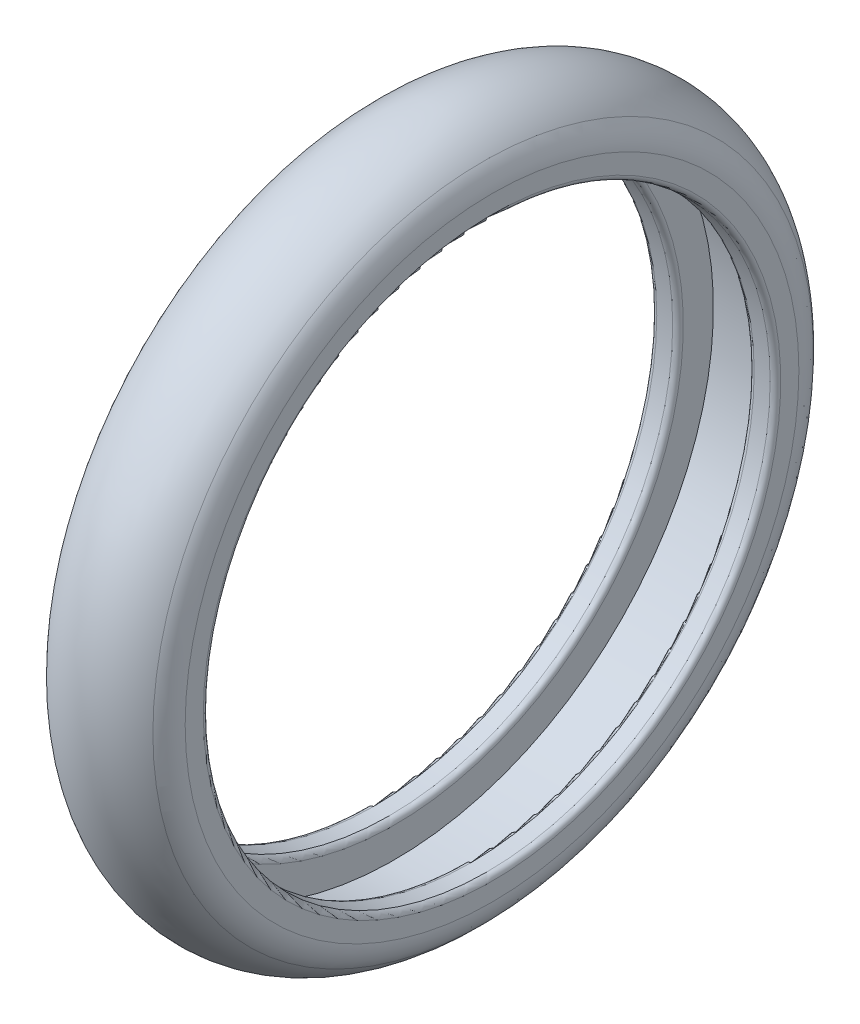
SolidWorks part; units mm, degrees
ref_plane "Ebene vorne" through (0, 0, 0) normal (0, 0, 1) x (1, 0, 0)
ref_plane "Ebene oben" through (0, 0, 0) normal (0, 1, 0) x (1, 0, 0)
ref_plane "Ebene rechts" through (0, 0, 0) normal (1, 0, 0) x (0, 0, -1)
sketch "Skizze2" plane through (0, 0, 0) normal (0, 0, 1) x (1, 0, 0)
  line L0 (0, 0) -> (0, 18) construction
  line L1 (2, 18) -> (-2, 18)
  line L2 (-2, 18) -> (-2, 16)
  line L3 (-2, 16) -> (-3.5, 16)
  line L4 (-3.5, 16) -> (-3.5, 17.9365)
  line L5 (3.5, 16) -> (3.5, 17.9365)
  line L6 (2, 16) -> (3.5, 16)
  line L7 (2, 18) -> (2, 16)
  line L8 (0, 0) -> (5.4917, 0) construction
  arc A0 (-3.5, 17.9365) -> (3.5, 17.9365) centre (0, 16) cw
  dimension "D2" = 4
  dimension "D6" = 16
  dimension "D1" = 32
  dimension "D3" = 7
  dimension "D4" = 4
  dimension "D5" = 2
revolve "Rotation1" add sketch "Skizze2" angle 360 about L8
fillet "Verrundung1" radius 2 2 edges at (-3.5, 0, 17.9365) (3.5, 0, 17.9365)
fillet "Verrundung2" radius 0.3 4 edges at (2, 0, 16) (-2, 0, 16) (-3.5, 0, 16) (3.5, 0, 16)
